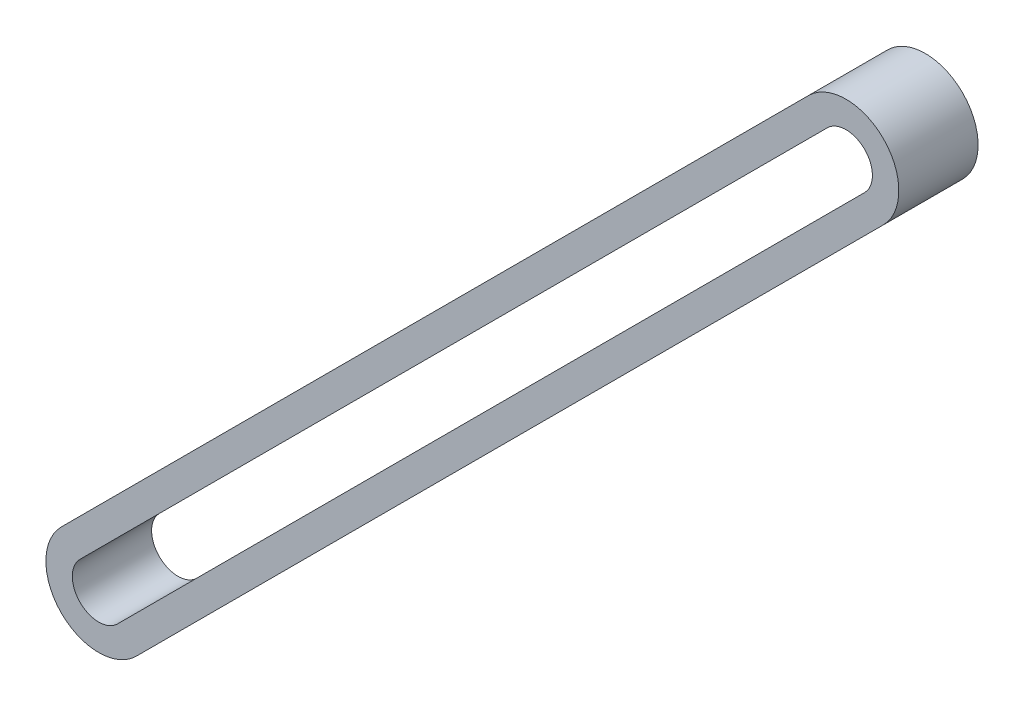
SolidWorks part; units mm, degrees
ref_plane "Front Plane" through (0, 0, 0) normal (0, 0, 1) x (1, 0, 0)
ref_plane "Top Plane" through (0, 0, 0) normal (0, 1, 0) x (1, 0, 0)
ref_plane "Right Plane" through (0, 0, 0) normal (1, 0, 0) x (0, 0, -1)
sketch "Sketch1" plane through (0, 0, 0) normal (0, 0, 1) x (1, 0, 0)
  line L0 (0, 0) -> (28.2843, 28.2843) construction
  line L1 (-1.4142, 1.4142) -> (26.8701, 29.6985)
  line L2 (1.4142, -1.4142) -> (29.6985, 26.8701)
  line L3 (-0.7071, 0.7071) -> (27.5772, 28.9914)
  line L4 (0.7071, -0.7071) -> (28.9914, 27.5772)
  line L5 (0, 0) -> (47.2301, 0) construction
  arc A0 (-1.4142, 1.4142) -> (1.4142, -1.4142) centre (0, 0) ccw
  arc A1 (29.6985, 26.8701) -> (26.8701, 29.6985) centre (28.2843, 28.2843) ccw
  arc A2 (28.9914, 27.5772) -> (27.5772, 28.9914) centre (28.2843, 28.2843) ccw
  arc A3 (-0.7071, 0.7071) -> (0.7071, -0.7071) centre (0, 0) ccw
  point P3 (14.1421, 14.1421)
  dimension "D2" = 2
  dimension "D1" = 40
  dimension "D4" = 45
  dimension "D3" = 1
extrude "Boss-Extrude1" add sketch "Sketch1" along normal blind 3
